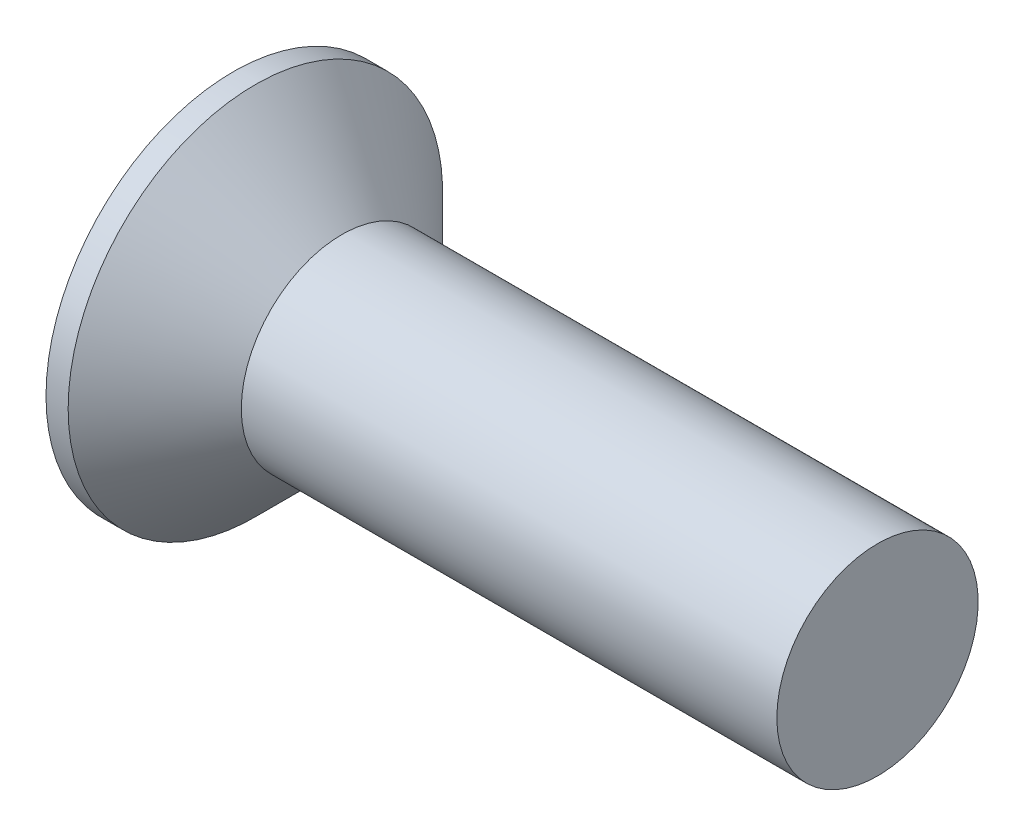
SolidWorks part; units mm, degrees
ref_plane "Plan de face" through (0, 0, 0) normal (0, 0, 1) x (1, 0, 0)
ref_plane "Plan de dessus" through (0, 0, 0) normal (0, 1, 0) x (1, 0, 0)
ref_plane "Plan de droite" through (0, 0, 0) normal (1, 0, 0) x (0, 0, -1)
sketch "Esquisse1" plane through (0, 0, 0) normal (0, 0, 1) x (1, 0, 0)
  line L0 (0, 0) -> (16, 0)
  line L1 (16, 0) -> (16, 2.5)
  line L2 (16, 2.5) -> (2.7, 2.5)
  line L4 (0, 4.65) -> (0, 0)
  line L5 (0, 4.65) -> (0.55, 4.65)
  line L6 (0.55, 4.65) -> (2.7, 2.5)
  dimension "D1" = 16
  dimension "D2" = 2.5
  dimension "D3" = 4.65
  dimension "D4" = 45
  dimension "D5" = 2.7
revolve "Révolution1" add sketch "Esquisse1" angle 360 about L0
equation "\"D3@Esquisse1\"=9.3/2"
